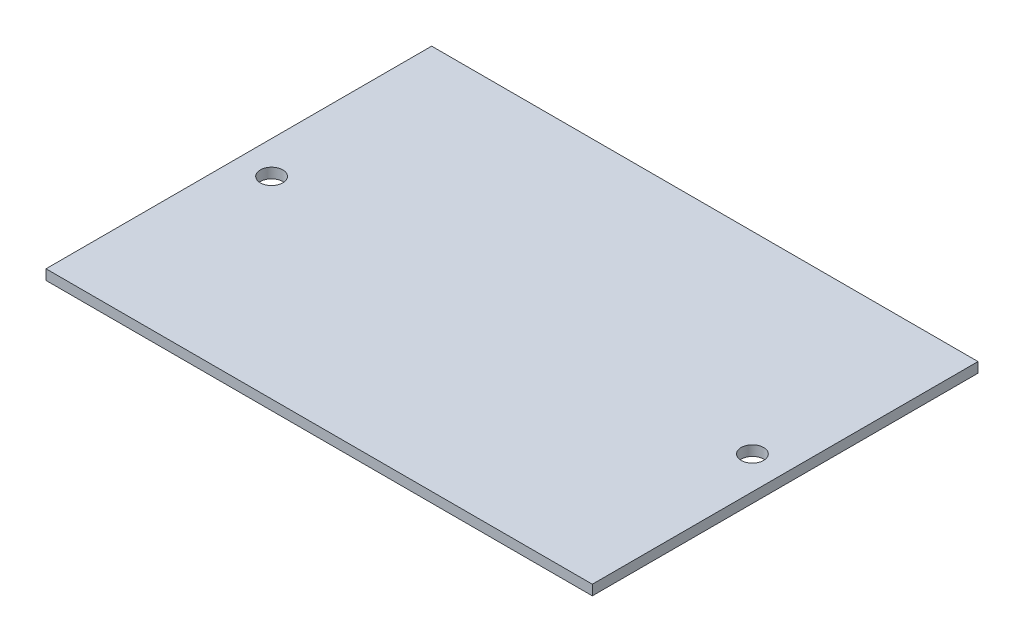
SolidWorks part; units mm, degrees
ref_plane "Front Plane" through (0, 0, 0) normal (0, 0, 1) x (1, 0, 0)
ref_plane "Top Plane" through (0, 0, 0) normal (0, 1, 0) x (1, 0, 0)
ref_plane "Right Plane" through (0, 0, 0) normal (1, 0, 0) x (0, 0, -1)
sketch "Sketch1" plane through (0, 0, 0) normal (0, 1, 0) x (1, 0, 0)
  line L1 (-43.18, 30.48) -> (43.18, 30.48)
  line L2 (-43.18, 30.48) -> (-43.18, -30.48)
  line L3 (-43.18, -30.48) -> (43.18, -30.48)
  line L4 (43.18, 30.48) -> (43.18, -30.48)
  line L5 (-43.18, 30.48) -> (43.18, -30.48) construction
  line L6 (-43.18, -30.48) -> (43.18, 30.48) construction
  point P0 (0, 0)
  dimension "D1" = 86.36
  dimension "D2" = 60.96
extrude "Boss-Extrude1" add sketch "Sketch1" along normal blind 1.6
sketch "Sketch2" plane through (0, 1.6, 0) normal (0, 1, 0) x (1, 0, 0)
  line L0 (-38, 0) -> (38, 0) construction
  circle A0 centre (-38, 0) radius 1.778
  circle A1 centre (38, 0) radius 1.778
  point P4 (0, 0)
  dimension "D1" = 3.556
  dimension "D2" = 38
extrude "Cut-Extrude1" cut sketch "Sketch2" against normal up to next
